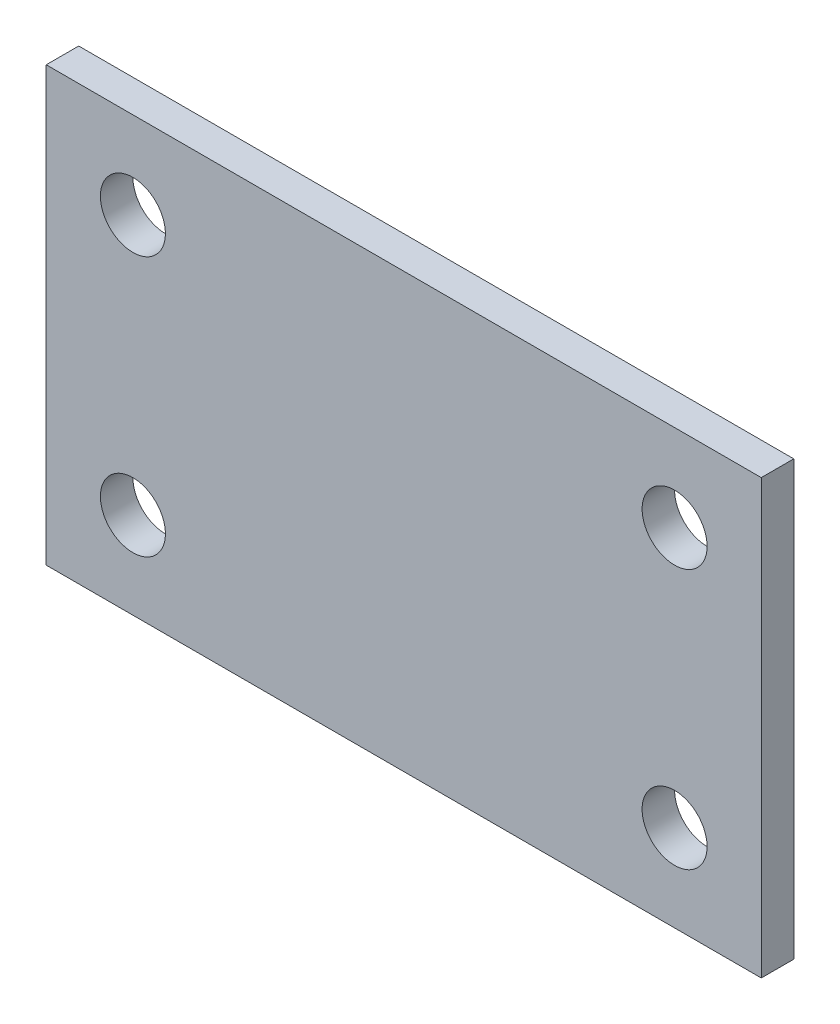
SolidWorks part; units mm, degrees
material "Thornel Mat VMA"
ref_plane "前视基准面" through (0, 0, 0) normal (0, 0, 1) x (1, 0, 0)
ref_plane "上视基准面" through (0, 0, 0) normal (0, 1, 0) x (1, 0, 0)
ref_plane "右视基准面" through (0, 0, 0) normal (1, 0, 0) x (0, 0, -1)
sketch "草图1" plane through (0, 0, 0) normal (0, 0, 1) x (1, 0, 0)
  line L0 (0, -20) -> (0, 20) construction
  line L1 (-33, 20) -> (33, 20)
  line L2 (-33, 20) -> (-33, -20)
  line L3 (-33, -20) -> (33, -20)
  line L4 (33, 20) -> (33, -20)
  circle A0 centre (25, 12) radius 3
  circle A1 centre (25, -12) radius 3
  circle A2 centre (-25, -12) radius 3
  circle A3 centre (-25, 12) radius 3
  point P8 (0, -20)
  point P10 (-33, 0)
  point P13 (0, 0)
  dimension "D3" = 6
  dimension "D1" = 40
  dimension "D2" = 66
  dimension "D4" = 24
  dimension "D5" = 8
  dimension "D6" = 50
extrude "凸台-拉伸1" add sketch "草图1" along normal blind 3
